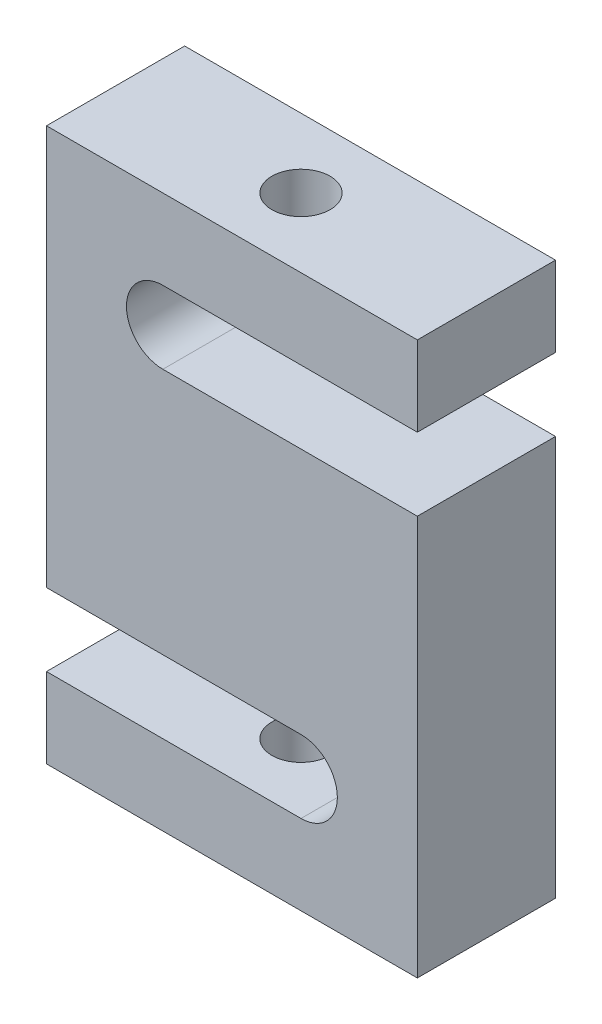
SolidWorks part; units mm, degrees
ref_plane "前视基准面" through (0, 0, 0) normal (0, 0, 1) x (1, 0, 0)
ref_plane "上视基准面" through (0, 0, 0) normal (0, 1, 0) x (1, 0, 0)
ref_plane "右视基准面" through (0, 0, 0) normal (1, 0, 0) x (0, 0, -1)
sketch "草图1" plane through (0, 0, 0) normal (0, 0, 1) x (1, 0, 0)
  line L1 (-25.5, -38) -> (25.5, -38)
  line L2 (-25.5, -38) -> (-25.5, 38)
  line L3 (-25.5, 38) -> (25.5, 38)
  line L4 (25.5, -38) -> (25.5, 38)
  line L5 (-25.5, -38) -> (25.5, 38) construction
  line L6 (-25.5, 38) -> (25.5, -38) construction
  point P0 (0, 0)
  dimension "D1" = 76
  dimension "D2" = 51
extrude "凸台-拉伸1" add sketch "草图1" along normal blind 19
sketch "草图3" plane through (0, 0, 0) normal (0, 0, -1) x (-1, 0, 0)
  line L0 (0, 0) -> (50000, 0) construction
  line L1 (-25.5, 27) -> (9.5, 27)
  line L2 (-25.5, -38) -> (-25.5, 38) construction
  line L3 (9.5, 27) -> (9.5, 17) construction
  line L4 (9.5, 17) -> (-25.5, 17)
  line L5 (-25.5, 17) -> (-25.5, 27)
  line L6 (25.5, 38) -> (25.5, -38) construction
  line L10 (0, 0) -> (0, -50000) construction
  line L11 (-9.5, -27) -> (-9.5, -17) construction
  line L12 (25.5, -27) -> (-9.5, -27)
  line L13 (-9.5, -17) -> (25.5, -17)
  line L14 (25.5, -17) -> (25.5, -27)
  line L15 (-25.5, 38) -> (25.5, 38) construction
  line L16 (25.5, -38) -> (-25.5, -38) construction
  arc A0 (9.5, 17) -> (9.5, 27) centre (9.5, 22) ccw
  arc A2 (-9.5, -17) -> (-9.5, -27) centre (-9.5, -22) ccw
  dimension "D1" = 10
  dimension "D6" = 5
  dimension "D2" = 11
  dimension "D3" = 35
  dimension "D4" = 11
  dimension "D5" = 35
extrude "切除-拉伸2" cut sketch "草图3" against normal through all
sketch "草图2" plane through (0, 38, 0) normal (0, 1, 0) x (1, 0, 0)
  line L0 (0, 0) -> (0, -50000) construction
  line L1 (-25.5, -9.5) -> (49974.5, -9.5) construction
  line L2 (-25.5, -19) -> (-25.5, 0) construction
  circle A0 centre (0, -9.5) radius 4
  point P7 (-25.5, -9.5)
  dimension "D1" = 8
extrude "切除-拉伸1" cut sketch "草图2" against normal blind 19
mirror "镜向1" about plane through (0, 0, 0) normal (0, 1, 0) of "切除-拉伸1"
